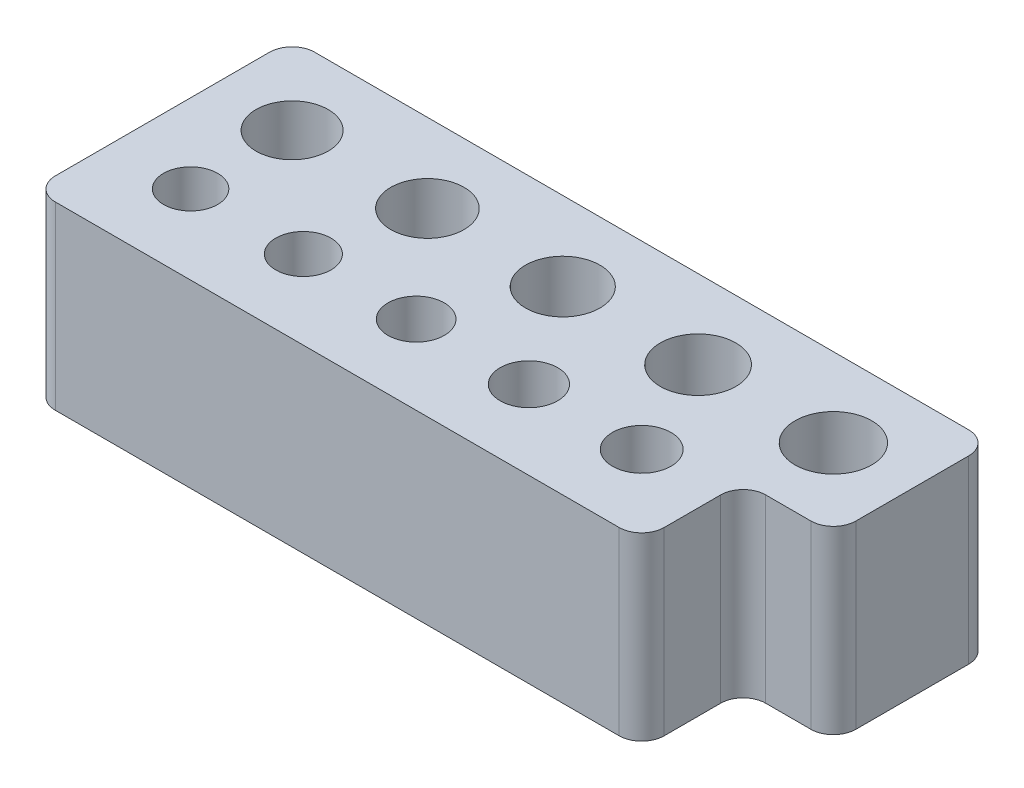
SolidWorks part; units mm, degrees
ref_plane "Front Plane" through (0, 0, 0) normal (0, 0, 1) x (1, 0, 0)
ref_plane "Top Plane" through (0, 0, 0) normal (0, 1, 0) x (1, 0, 0)
ref_plane "Right Plane" through (0, 0, 0) normal (1, 0, 0) x (0, 0, -1)
sketch "Sketch1" plane through (0, 0, 0) normal (0, 1, 0) x (1, 0, 0)
  line L0 (3.5, 3.5) -> (23.5, 3.5) construction
  line L1 (0, 0) -> (27, 0)
  line L2 (0, 0) -> (0, 11.5)
  line L3 (0, 11.5) -> (31, 11.5)
  line L4 (31, 4.5) -> (31, 11.5)
  line L5 (3.5, 8) -> (27.5, 8) construction
  line L6 (27, 0) -> (27, 4.5)
  line L7 (27, 4.5) -> (31, 4.5)
  circle A0 centre (3.5, 3.5) radius 1.2
  circle A1 centre (8.5, 3.5) radius 1.225
  circle A2 centre (13.5, 3.5) radius 1.25
  circle A3 centre (18.5, 3.5) radius 1.275
  circle A4 centre (23.5, 3.5) radius 1.3
  circle A5 centre (3.5, 8) radius 1.6
  circle A6 centre (9.5, 8) radius 1.625
  circle A7 centre (15.5, 8) radius 1.65
  circle A8 centre (21.5, 8) radius 1.675
  circle A9 centre (27.5, 8) radius 1.7
  dimension "D1" = 2.4
  dimension "D2" = 2.45
  dimension "D3" = 2.5
  dimension "D4" = 2.55
  dimension "D5" = 2.6
  dimension "D6" = 3.2
  dimension "D7" = 3.25
  dimension "D8" = 3.3
  dimension "D9" = 3.35
  dimension "D10" = 3.4
  dimension "D13" = 5
  dimension "D14" = 5
  dimension "D15" = 5
  dimension "D16" = 5
  dimension "D18" = 6
  dimension "D19" = 6
  dimension "D20" = 6
  dimension "D21" = 6
  dimension "D23" = 3.5
  dimension "D24" = 3.5
  dimension "D11" = 3.5
  dimension "D12" = 3.5
  dimension "D17" = 4.5
  dimension "D22" = 3.5
  dimension "D25" = 3.5
extrude "Boss-Extrude1" add sketch "Sketch1" along normal blind 8
fillet "Fillet1" radius 1 6 edges at (0, 4, -11.5) (31, 4, -11.5) (31, 4, -4.5) (27, 4, -4.5) (27, 4, 0) (0, 4, 0)
